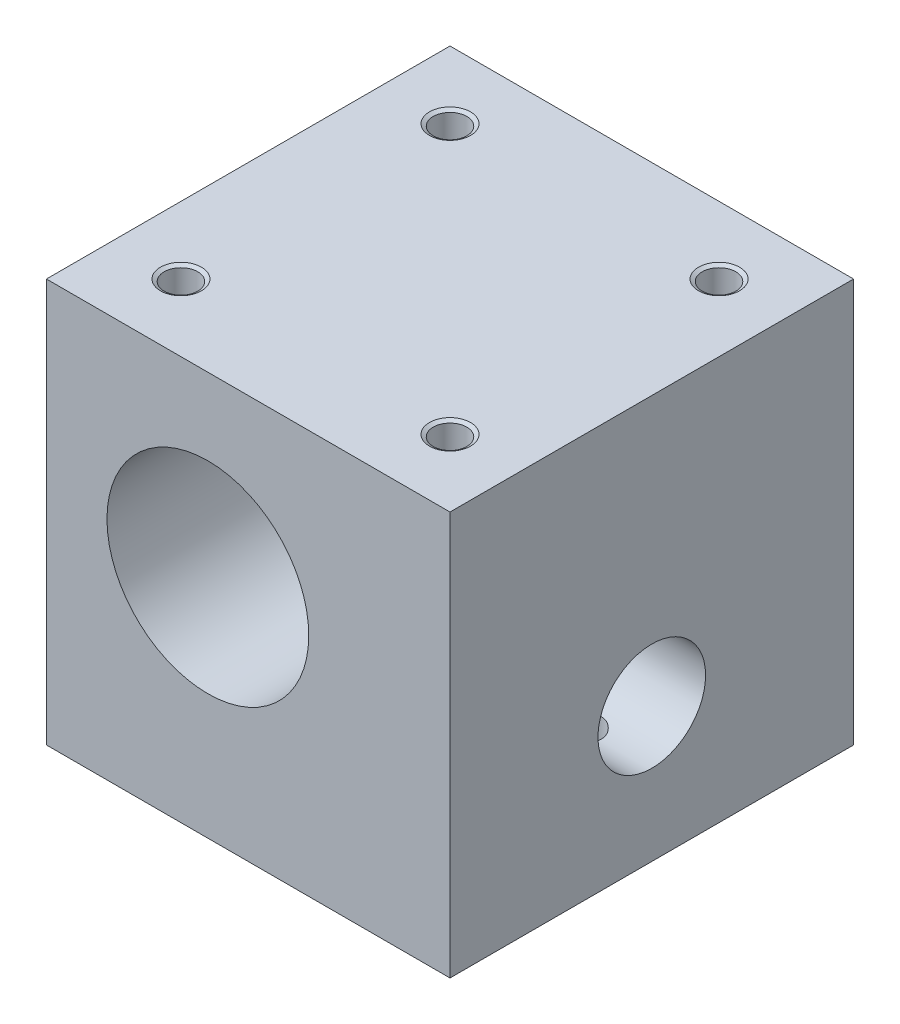
SolidWorks part; units mm, degrees
material "Lega 1060"
ref_plane "Piano frontale" through (0, 0, 0) normal (0, 0, 1) x (1, 0, 0)
ref_plane "Piano superiore" through (0, 0, 0) normal (0, 1, 0) x (1, 0, 0)
ref_plane "Piano destro" through (0, 0, 0) normal (1, 0, 0) x (0, 0, -1)
sketch "Schizzo1" plane through (0, 0, 0) normal (0, 0, 1) x (1, 0, 0)
  line L0 (12, 6.5764) -> (12, 28.444) construction
  line L1 (0, 0) -> (30, 0)
  line L2 (0, 0) -> (0, 30)
  line L3 (0, 30) -> (30, 30)
  line L4 (30, 0) -> (30, 30)
  line L5 (6.315, 16.8) -> (24.6155, 16.8) construction
  circle A0 centre (12, 16.8) radius 7.5
  dimension "D3" = 15
  dimension "D1" = 30
  dimension "D2" = 30
  dimension "D4" = 12
  dimension "D5" = 13.2
extrude "Estrusione-Estrusione1" add sketch "Schizzo1" along normal blind 30
sketch "Schizzo3" plane through (30, 0, 0) normal (1, 0, 0) x (0, 0, -1)
  line L2 (-15, 10.16) -> (-15, 24.3684) construction
  line L3 (-30, 0) -> (-30, 30) construction
  line L4 (0, 0) -> (0, 30) construction
  line L5 (-30, 0) -> (0, 0) construction
  point P0 (-15, 10)
  dimension "D1" = 10
hole_wizard "Foro Ø8.0 (8)-1" positions "Schizzo5" profile "Schizzo4" hole size "Ø8.0" standard "ISO"
sketch "Schizzo5" plane through (30, 0, 0) normal (1, 0, 0) x (0, 0, -1)
  point P0 (-15, 10)
sketch "Schizzo4" plane through (30, 10, 15) normal (0, 1, 0) x (0, 0, -1)
  line L0 (0, 0) -> (0, 12.4034)
  line L1 (0, 12.4034) -> (4, 10)
  line L2 (4, 10) -> (4, 0)
  line L5 (4, 0) -> (0, 0)
  line L10 (0, 12.4034) -> (-4, 10) construction
  line L11 (0, -6.35) -> (0, 107.95) construction
  dimension "Hole Dia." = 8
  dimension "Hole Depth" = 10
  dimension "Drill Angle" = 118
sketch "Schizzo6" plane through (0, 30, 0) normal (0, 1, 0) x (1, 0, 0)
  line L0 (-7.6843, -25) -> (41.504, -25) construction
  line L1 (0, -30) -> (0, 0) construction
  line L2 (30, -30) -> (0, -30) construction
  point P0 (5, -25)
  point P1 (25, -25)
  dimension "D1" = 20
  dimension "D2" = 5
  dimension "D3" = 5
hole_wizard "Foro filettato M3-1" positions "Schizzo8" profile "Schizzo7" tap size "M3" standard "ISO"
sketch "Schizzo8" plane through (0, 30, 0) normal (0, 1, 0) x (1, 0, 0)
  point P0 (5, -25)
  point P3 (25, -25)
sketch "Schizzo7" plane through (5, 30, 25) normal (1, 0, 0) x (0, 0, 1)
  line L0 (0, 0) -> (0, 9.2511)
  line L1 (0, 9.2511) -> (1.25, 8.5)
  line L2 (1.25, 8.5) -> (1.25, 0.1588)
  line L3 (1.25, 0.1588) -> (1.525, 0)
  line L5 (1.525, 0) -> (0, 0)
  line L6 (-1.25, 0.1588) -> (-1.525, 0) construction
  line L10 (0, 9.2511) -> (-1.25, 8.5) construction
  line L11 (0, -6.35) -> (0, 107.95) construction
  dimension "Tap Drill Dia." = 2.5
  dimension "Tap Drill Depth" = 8.5
  dimension "Near C'Sink Dia." = 3.05
  dimension "Near C'Sink Angle" = 120
  dimension "Drill Angle" = 118
cosmetic thread "Filettatura del foro1" parameters "D1"=6, "D2"=3
cosmetic thread "Filettatura del foro2" parameters "D1"=6, "D2"=3
ref_plane "Piano1" through (0, 0, 15) normal (0, 0, 1) x (1, 0, 0)
mirror "Specchia1" about plane through (0, 0, 15) normal (0, 0, 1) of "Foro filettato M3-1"
hole_wizard "Foro filettato M3-2" positions "Schizzo10" profile "Schizzo11" tap size "M3" standard "ISO"
sketch "Schizzo10" plane through (0, 0, 0) normal (0, -1, 0) x (-1, 0, 0)
  line L0 (0, 0) -> (-30, 0) construction
  line L1 (-30, -30) -> (-30, 0) construction
  point P0 (-25, -15)
  dimension "D1" = 15
  dimension "D2" = 5
sketch "Schizzo11" plane through (25, 0, 15) normal (1, 0, 0) x (0, 0, -1)
  line L0 (0, 0) -> (0, 9.2511)
  line L1 (0, 9.2511) -> (1.25, 8.5)
  line L2 (1.25, 8.5) -> (1.25, 0.1588)
  line L3 (1.25, 0.1588) -> (1.525, 0)
  line L5 (1.525, 0) -> (0, 0)
  line L6 (-1.25, 0.1588) -> (-1.525, 0) construction
  line L10 (0, 9.2511) -> (-1.25, 8.5) construction
  line L11 (0, -6.35) -> (0, 107.95) construction
  dimension "Tap Drill Dia." = 2.5
  dimension "Tap Drill Depth" = 8.5
  dimension "Near C'Sink Dia." = 3.05
  dimension "Near C'Sink Angle" = 120
  dimension "Drill Angle" = 118
